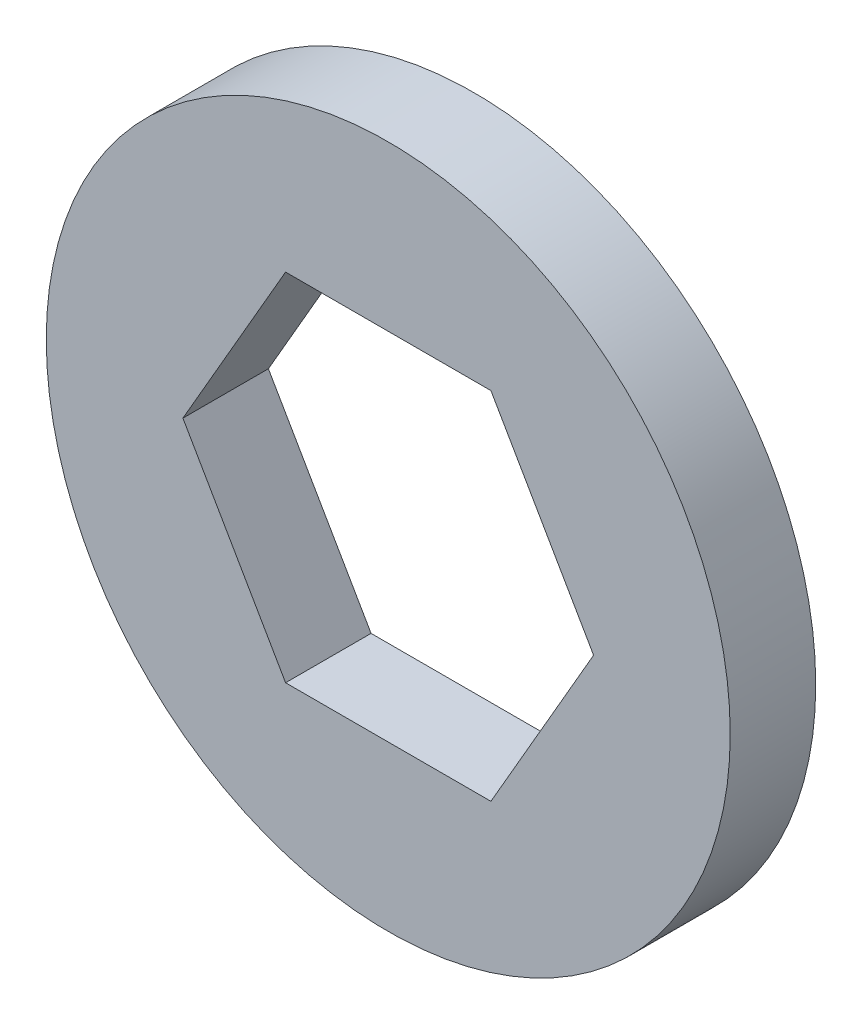
SolidWorks part; units mm, degrees
ref_plane "Front Plane" through (0, 0, 0) normal (0, 0, 1) x (1, 0, 0)
ref_plane "Top Plane" through (0, 0, 0) normal (0, 1, 0) x (1, 0, 0)
ref_plane "Right Plane" through (0, 0, 0) normal (1, 0, 0) x (0, 0, -1)
sketch "Sketch1" plane through (0, 0, 0) normal (0, 0, 1) x (1, 0, 0)
  line L1 (3.8128, -6.604) -> (7.6256, 0)
  line L2 (7.6256, 0) -> (3.8128, 6.604)
  line L3 (3.8128, 6.604) -> (-3.8128, 6.604)
  line L4 (-3.8128, 6.604) -> (-7.6256, 0)
  line L5 (-7.6256, 0) -> (-3.8128, -6.604)
  line L6 (-3.8128, -6.604) -> (3.8128, -6.604)
  circle A0 centre (0, 0) radius 6.604 construction
  circle A1 centre (0, 0) radius 12.7
  dimension "D2" = 25.4
  dimension "D1" = 13.208
extrude "Boss-Extrude1" add sketch "Sketch1" along normal blind 3.175
